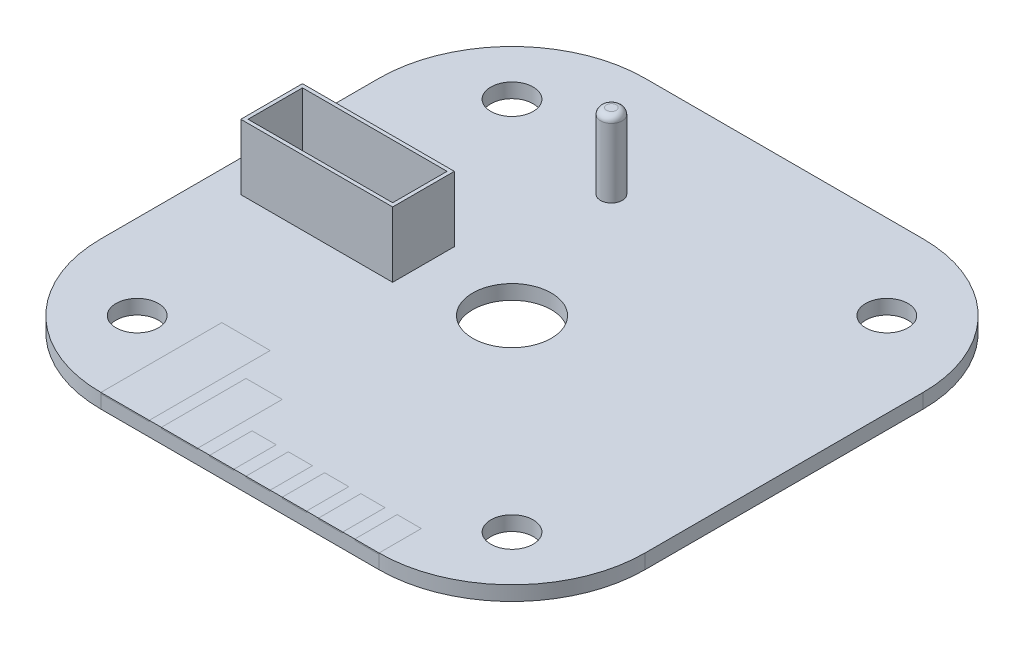
SolidWorks part; units mm, degrees
ref_plane "Front Plane" through (0, 0, 0) normal (0, 0, 1) x (1, 0, 0)
ref_plane "Top Plane" through (0, 0, 0) normal (0, 1, 0) x (1, 0, 0)
ref_plane "Right Plane" through (0, 0, 0) normal (1, 0, 0) x (0, 0, -1)
sketch "Sketch1" plane through (0, 0, 0) normal (0, 1, 0) x (1, 0, 0)
  line L1 (-22.5, -22.5) -> (22.5, -22.5)
  line L2 (-22.5, -22.5) -> (-22.5, 22.5)
  line L3 (-22.5, 22.5) -> (22.5, 22.5)
  line L4 (22.5, -22.5) -> (22.5, 22.5)
  line L5 (-22.5, -22.5) -> (22.5, 22.5) construction
  line L6 (-22.5, 22.5) -> (22.5, -22.5) construction
  point P0 (0, 0)
  dimension "D1" = 45
extrude "Boss-Extrude1" add sketch "Sketch1" along normal mid plane 1.2
sketch "Sketch3" plane through (0, 0, 0) normal (0, 1, 0) x (1, 0, 0)
  circle A0 centre (0, 0) radius 3.25
  dimension "D1" = 6.5
extrude "Cut-Extrude1" cut sketch "Sketch3" against normal through all both and the other way through all
fillet "Fillet1" radius 11 4 edges at (22.5, 0, 22.5) (-22.5, 0, 22.5) (-22.5, 0, -22.5) (22.5, 0, -22.5)
sketch "Sketch5" plane through (0, 0, 0) normal (0, 1, 0) x (1, 0, 0)
  line L0 (-15.5, -15.5) -> (15.5, 15.5) construction
  line L1 (-15.5, 15.5) -> (15.5, -15.5) construction
  line L2 (0, 0) -> (0, 21.9203) construction
  circle A0 centre (0, 0) radius 21.9203 construction
  circle A1 centre (-15.5, 15.5) radius 1.75
  circle A2 centre (15.5, 15.5) radius 1.75
  circle A3 centre (15.5, -15.5) radius 1.75
  circle A4 centre (-15.5, -15.5) radius 1.75
  point P6 (0, 0)
  point P9 (0, 0)
  dimension "D2" = 3.5
  dimension "D3" = 31
  dimension "D1" = 45
extrude "Cut-Extrude2" cut sketch "Sketch5" against normal through all both and the other way through all
sketch "Sketch6" plane through (0, 0.6, 0) normal (0, 1, 0) x (1, 0, 0)
  line L0 (-13.6, 0) -> (0, 0) construction
  line L1 (-19.88, -2.55) -> (-7.32, -2.55)
  line L2 (-19.88, -2.55) -> (-19.88, 2.55)
  line L3 (-19.88, 2.55) -> (-7.32, 2.55)
  line L4 (-7.32, -2.55) -> (-7.32, 2.55)
  line L5 (-19.88, -2.55) -> (-7.32, 2.55) construction
  line L6 (-19.88, 2.55) -> (-7.32, -2.55) construction
  point P0 (-13.6, 0)
  point P7 (-10.9788, 0)
  dimension "D3" = 13.6
  dimension "D1" = 12.56
  dimension "D2" = 5.1
extrude "Extrude-Thin1" add sketch "Sketch6" along normal blind 5.4 thin thin type one direction reverse wall 0.3
sketch "Sketch7" plane through (0, 0.6, 0) normal (0, 1, 0) x (1, 0, 0)
  line L0 (-7.62, -2.25) -> (-7.62, 2.25) construction
  line L1 (-19.58, -2.25) -> (-7.62, -2.25) construction
  line L2 (-19.58, 2.25) -> (-19.58, -2.25) construction
  line L3 (-7.62, 2.25) -> (-19.58, 2.25) construction
  line L4 (-7.62, -2.25) -> (-7.62, 2.25)
  line L5 (-19.58, -2.25) -> (-7.62, -2.25)
  line L6 (-19.58, 2.25) -> (-19.58, -2.25)
  line L7 (-7.62, 2.25) -> (-19.58, 2.25)
extrude "Boss-Extrude2" add sketch "Sketch7" along normal blind 0.3
sketch "Sketch8" plane through (0, 0.6, 0) normal (0, 1, 0) x (1, 0, 0)
  line L0 (-11.5, -22.5) -> (11.5, -22.5) construction
  line L1 (-2.5, -22.5) -> (-0.5, -22.5)
  line L2 (-2.5, -22.5) -> (-2.5, -19)
  line L3 (-2.5, -19) -> (-0.5, -19)
  line L4 (-0.5, -22.5) -> (-0.5, -19)
  line L5 (-0.5, -19) -> (0.5, -19) construction
  line L6 (0.5, -22.5) -> (2.5, -22.5)
  line L7 (0.5, -22.5) -> (0.5, -19)
  line L8 (0.5, -19) -> (2.5, -19)
  line L9 (2.5, -22.5) -> (2.5, -19)
  line L10 (3.5, -22.5) -> (5.5, -22.5)
  line L11 (3.5, -22.5) -> (3.5, -19)
  line L12 (3.5, -19) -> (5.5, -19)
  line L13 (5.5, -22.5) -> (5.5, -19)
  line L14 (6.5, -22.5) -> (8.5, -22.5)
  line L15 (6.5, -22.5) -> (6.5, -19)
  line L16 (6.5, -19) -> (8.5, -19)
  line L17 (8.5, -22.5) -> (8.5, -19)
  line L18 (9.5, -22.5) -> (11.5, -22.5)
  line L19 (9.5, -22.5) -> (9.5, -19)
  line L20 (9.5, -19) -> (11.5, -19)
  line L21 (11.5, -22.5) -> (11.5, -19)
  line L22 (2.5, -19) -> (3.5, -19) construction
  line L23 (5.5, -19) -> (6.5, -19) construction
  line L24 (8.5, -19) -> (9.5, -19) construction
  line L26 (-11.5, -22.5) -> (-7.5, -22.5)
  line L27 (-11.5, -22.5) -> (-11.5, -12.5)
  line L28 (-11.5, -12.5) -> (-7.5, -12.5)
  line L29 (-7.5, -22.5) -> (-7.5, -12.5)
  line L30 (-6.5, -22.5) -> (-3.5, -22.5)
  line L31 (-6.5, -22.5) -> (-6.5, -15.5)
  line L32 (-6.5, -15.5) -> (-3.5, -15.5)
  line L33 (-3.5, -22.5) -> (-3.5, -15.5)
  dimension "D1" = 2
  dimension "D2" = 1
  dimension "D3" = 3.5
  dimension "D4" = 10
  dimension "D5" = 4
  dimension "D6" = 1
  dimension "D7" = 3
  dimension "D8" = 7
  dimension "D9" = 1
extrude "Cut-Extrude3" cut sketch "Sketch8" against normal blind 0.1
sketch "Sketch9" plane through (0, 0.5, 0) normal (0, 1, 0) x (1, 0, 0)
  line L0 (9.5, -19) -> (9.5, -22.5) construction
  line L1 (9.5, -22.5) -> (11.5, -22.5) construction
  line L2 (11.5, -22.5) -> (11.5, -19) construction
  line L3 (11.5, -19) -> (9.5, -19) construction
  line L4 (6.5, -19) -> (6.5, -22.5) construction
  line L5 (6.5, -22.5) -> (8.5, -22.5) construction
  line L6 (8.5, -22.5) -> (8.5, -19) construction
  line L7 (8.5, -19) -> (6.5, -19) construction
  line L8 (3.5, -19) -> (3.5, -22.5) construction
  line L9 (3.5, -22.5) -> (5.5, -22.5) construction
  line L10 (5.5, -22.5) -> (5.5, -19) construction
  line L11 (5.5, -19) -> (3.5, -19) construction
  line L12 (0.5, -19) -> (0.5, -22.5) construction
  line L13 (0.5, -22.5) -> (2.5, -22.5) construction
  line L14 (2.5, -22.5) -> (2.5, -19) construction
  line L15 (2.5, -19) -> (0.5, -19) construction
  line L16 (-2.5, -19) -> (-2.5, -22.5) construction
  line L17 (-2.5, -22.5) -> (-0.5, -22.5) construction
  line L18 (-0.5, -22.5) -> (-0.5, -19) construction
  line L19 (-0.5, -19) -> (-2.5, -19) construction
  line L20 (-6.5, -15.5) -> (-6.5, -22.5) construction
  line L21 (-6.5, -22.5) -> (-3.5, -22.5) construction
  line L22 (-3.5, -22.5) -> (-3.5, -15.5) construction
  line L23 (-3.5, -15.5) -> (-6.5, -15.5) construction
  line L24 (-11.5, -12.5) -> (-11.5, -22.5) construction
  line L25 (-11.5, -22.5) -> (-7.5, -22.5) construction
  line L26 (-7.5, -22.5) -> (-7.5, -12.5) construction
  line L27 (-7.5, -12.5) -> (-11.5, -12.5) construction
  line L28 (9.5, -19) -> (9.5, -22.5)
  line L29 (9.5, -22.5) -> (11.5, -22.5)
  line L30 (11.5, -22.5) -> (11.5, -19)
  line L31 (11.5, -19) -> (9.5, -19)
  line L32 (6.5, -19) -> (6.5, -22.5)
  line L33 (6.5, -22.5) -> (8.5, -22.5)
  line L34 (8.5, -22.5) -> (8.5, -19)
  line L35 (8.5, -19) -> (6.5, -19)
  line L36 (3.5, -19) -> (3.5, -22.5)
  line L37 (3.5, -22.5) -> (5.5, -22.5)
  line L38 (5.5, -22.5) -> (5.5, -19)
  line L39 (5.5, -19) -> (3.5, -19)
  line L40 (0.5, -19) -> (0.5, -22.5)
  line L41 (0.5, -22.5) -> (2.5, -22.5)
  line L42 (2.5, -22.5) -> (2.5, -19)
  line L43 (2.5, -19) -> (0.5, -19)
  line L44 (-2.5, -19) -> (-2.5, -22.5)
  line L45 (-2.5, -22.5) -> (-0.5, -22.5)
  line L46 (-0.5, -22.5) -> (-0.5, -19)
  line L47 (-0.5, -19) -> (-2.5, -19)
  line L48 (-6.5, -15.5) -> (-6.5, -22.5)
  line L49 (-6.5, -22.5) -> (-3.5, -22.5)
  line L50 (-3.5, -22.5) -> (-3.5, -15.5)
  line L51 (-3.5, -15.5) -> (-6.5, -15.5)
  line L52 (-11.5, -12.5) -> (-11.5, -22.5)
  line L53 (-11.5, -22.5) -> (-7.5, -22.5)
  line L54 (-7.5, -22.5) -> (-7.5, -12.5)
  line L55 (-7.5, -12.5) -> (-11.5, -12.5)
extrude "Boss-Extrude3" add sketch "Sketch9" along normal up to surface (0.1 mm away) separate body up to face at (-15.5, 0.6, 17.25)
sketch "Sketch10" plane through (0, 0.6, 0) normal (0, 1, 0) x (1, 0, 0)
  line L0 (-2.5, -9.5) -> (-2.5, -13.6) construction
  line L1 (3.5, -9.5) -> (3.5, -13.6) construction
  line L2 (-2.5, -11.55) -> (3.5, -11.55) construction
  circle A0 centre (3.5, -9.5) radius 0.9 construction
  circle A1 centre (3.5, -13.6) radius 1.65 construction
  circle A2 centre (-2.5, -13.6) radius 1.65 construction
  circle A3 centre (-2.5, -9.5) radius 0.9 construction
  circle A4 centre (-4.59, 12.81) radius 0.9
  circle A5 centre (-15.5, 15.5) radius 1.75 construction
  circle A6 centre (0, 0) radius 3.25 construction
  point P16 (-4.7203, 13)
  dimension "D1" = 1.8
  dimension "D2" = 3.3
  dimension "D3" = 19
  dimension "D4" = 25
  dimension "D5" = 29.1
  dimension "D6" = 4.59
  dimension "D7" = 13
  dimension "D8" = 12.81
extrude "Boss-Extrude4" add sketch "Sketch10" along normal blind 6.2
fillet "Fillet2" radius 0.5 1 edges at (-4.59, 6.8, -11.91)
